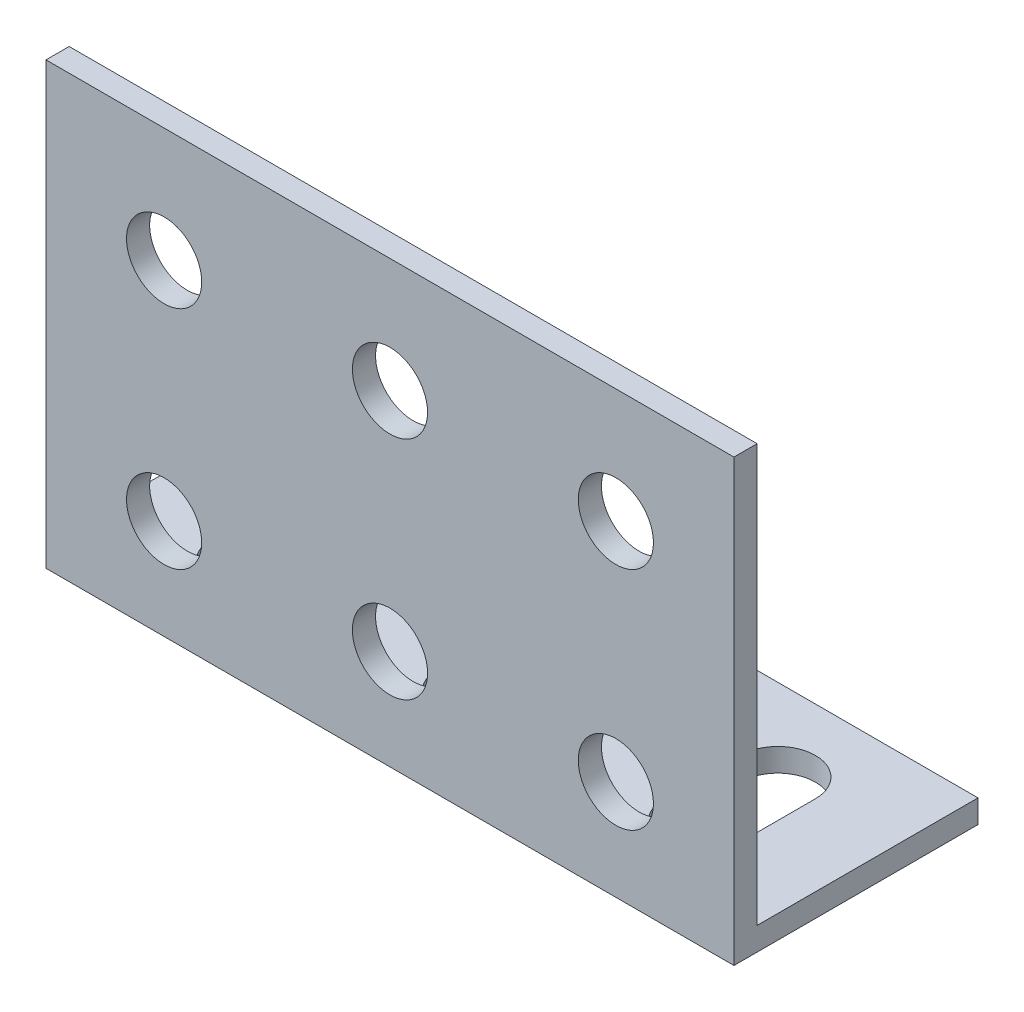
SolidWorks part; units mm, degrees
ref_plane "Front Plane" through (0, 0, 0) normal (0, 0, 1) x (1, 0, 0)
ref_plane "Top Plane" through (0, 0, 0) normal (0, 1, 0) x (1, 0, 0)
ref_plane "Right Plane" through (0, 0, 0) normal (1, 0, 0) x (0, 0, -1)
sketch "Sketch1" plane through (0, 0, 0) normal (0, 0, 1) x (1, 0, 0)
  line L1 (-40.5821, 17.3565) -> (-1.9621, 17.3565)
  line L2 (-40.5821, 17.3565) -> (-40.5821, -7.3635)
  line L3 (-40.5821, -7.3635) -> (-1.9621, -7.3635)
  line L4 (-1.9621, 17.3565) -> (-1.9621, -7.3635)
  circle A0 centre (-33.9521, 10.9265) radius 2.11
  circle A1 centre (-21.2721, 10.9265) radius 2.11
  circle A2 centre (-8.5921, 10.9265) radius 2.11
  circle A3 centre (-21.2721, -1.7535) radius 2.11
  circle A4 centre (-8.5921, -1.7535) radius 2.11
  circle A5 centre (-33.9521, -1.7535) radius 2.11
  point P16 (-36.0621, 10.9265)
  point P17 (-6.4821, 10.9265)
  point P18 (-21.2721, 13.0365)
  point P19 (-21.2721, -3.8635)
  dimension "D1" = 4.22
  dimension "D4" = 4.52
  dimension "D5" = 4.52
  dimension "D6" = 4.32
  dimension "D7" = 3.5
  dimension "D2" = 3
  dimension "D3" = 2
extrude "Boss-Extrude1" add sketch "Sketch1" against normal blind 1.3
sketch "Sketch2" plane through (0, -7.3635, 0) normal (0, -1, 0) x (1, 0, 0)
  line L0 (13.596, 0) -> (-13.596, 0) construction
  line L1 (-40.5821, 0) -> (-1.9621, 0)
  line L2 (-40.5821, 0) -> (-40.5821, -13.7)
  line L3 (-40.5821, -13.7) -> (-1.9621, -13.7)
  line L4 (-1.9621, 0) -> (-1.9621, -13.7)
  line L5 (-40.5821, -1.3) -> (-40.5821, 0) construction
  line L6 (-1.9621, -1.3) -> (-1.9621, 0) construction
  line L7 (-33.9521, -4.7914) -> (-33.9521, -9.0914) construction
  line L8 (-31.8421, -4.7914) -> (-31.8421, -9.0914)
  line L9 (-36.0621, -4.7914) -> (-36.0621, -9.0914)
  line L10 (-21.2721, -4.7914) -> (-21.2721, -9.0914) construction
  line L11 (-19.1621, -4.7914) -> (-19.1621, -9.0914)
  line L12 (-23.3821, -4.7914) -> (-23.3821, -9.0914)
  line L13 (-8.5921, -4.7914) -> (-8.5921, -9.0914) construction
  line L14 (-6.4821, -4.7914) -> (-6.4821, -9.0914)
  line L15 (-10.7021, -4.7914) -> (-10.7021, -9.0914)
  arc A0 (-31.8421, -4.7914) -> (-36.0621, -4.7914) centre (-33.9521, -4.7914) ccw
  arc A1 (-36.0621, -9.0914) -> (-31.8421, -9.0914) centre (-33.9521, -9.0914) ccw
  arc A2 (-19.1621, -4.7914) -> (-23.3821, -4.7914) centre (-21.2721, -4.7914) ccw
  arc A3 (-23.3821, -9.0914) -> (-19.1621, -9.0914) centre (-21.2721, -9.0914) ccw
  arc A4 (-6.4821, -4.7914) -> (-10.7021, -4.7914) centre (-8.5921, -4.7914) ccw
  arc A5 (-10.7021, -9.0914) -> (-6.4821, -9.0914) centre (-8.5921, -9.0914) ccw
  point P8 (-33.9521, -6.9414)
  point P17 (-33.9521, -2.6814)
  point P18 (-33.9521, -11.2014)
  point P20 (-21.2721, -6.9414)
  point P27 (-8.5921, -6.9414)
  dimension "D1" = 8.52
  dimension "D2" = 4.22
  dimension "D3" = 13.7
  dimension "D5" = 8.46
  dimension "D6" = 4.52
  dimension "D7" = 2.4986
  dimension "D4" = 3
extrude "Boss-Extrude2" add sketch "Sketch2" against normal blind 1.3
